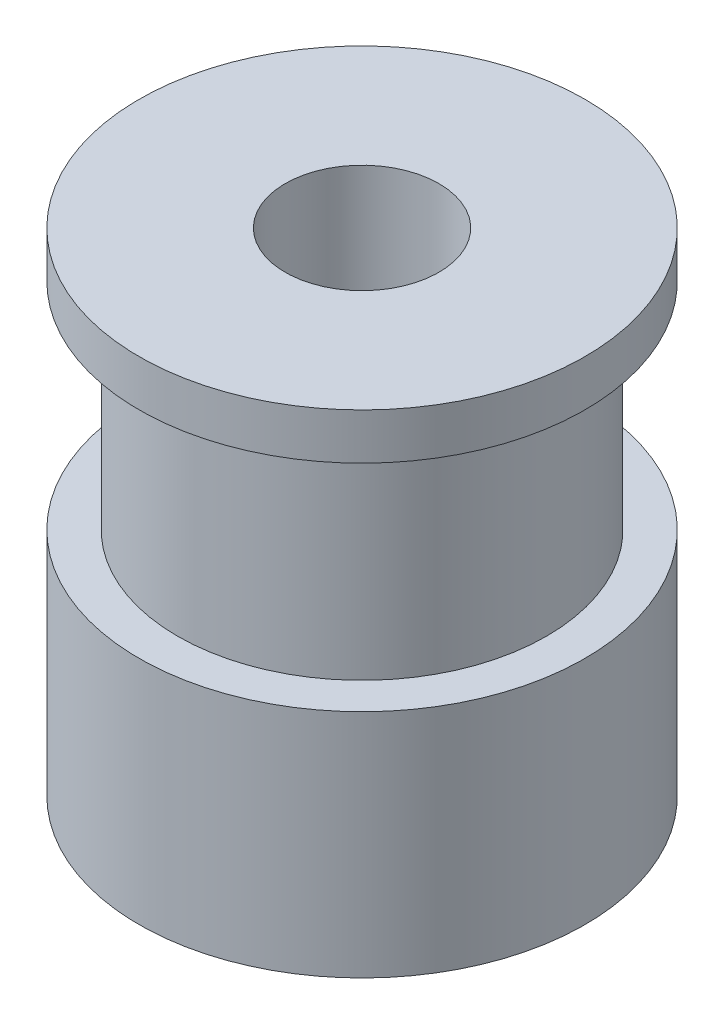
SolidWorks part; units mm, degrees
ref_plane "Спереди" through (0, 0, 0) normal (0, 0, 1) x (1, 0, 0)
ref_plane "Сверху" through (0, 0, 0) normal (0, 1, 0) x (1, 0, 0)
ref_plane "Справа" through (0, 0, 0) normal (1, 0, 0) x (0, 0, -1)
sketch "Эскиз3" plane through (0, 0, 0) normal (0, 0, 1) x (1, 0, 0)
  line L0 (0, 0) -> (0, 13.2083) construction
  line L1 (2.5, 0) -> (2.5, 16)
  line L2 (2.5, 16) -> (7.25, 16)
  line L3 (7.25, 16) -> (7.25, 14.5)
  line L4 (7.25, 14.5) -> (6, 14.5)
  line L5 (6, 14.5) -> (6, 7.5)
  line L6 (6, 7.5) -> (7.25, 7.5)
  line L7 (7.25, 7.5) -> (7.25, 0)
  line L8 (7.25, 0) -> (2.5, 0)
  dimension "D1" = 2.5
  dimension "D2" = 16
  dimension "D3" = 1.5
  dimension "D4" = 7
  dimension "D5" = 6
revolve "Повернуть1" add sketch "Эскиз3" angle 360 about L0
